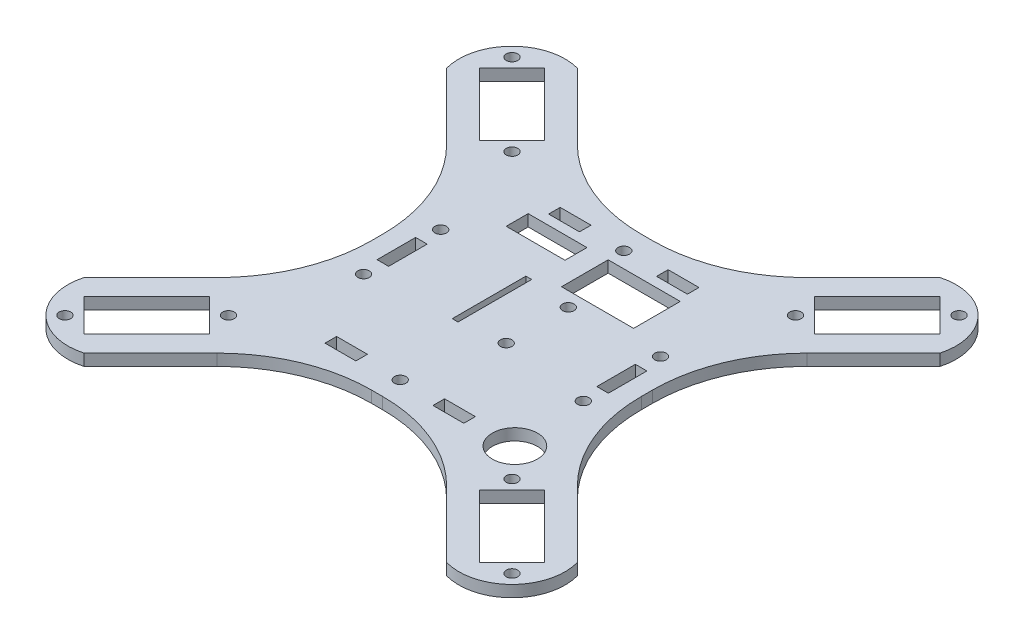
SolidWorks part; units mm, degrees
material "Pinho"
ref_plane "Plano frontal" through (0, 0, 0) normal (0, 0, 1) x (1, 0, 0)
ref_plane "Plano superior" through (0, 0, 0) normal (0, 1, 0) x (1, 0, 0)
ref_plane "Plano direito" through (0, 0, 0) normal (1, 0, 0) x (0, 0, -1)
sketch "Esboço1" plane through (0, 0, 0) normal (0, 1, 0) x (1, 0, 0)
  line L1 (84.8478, -7) -> (84.8478, 3)
  line L2 (121.8478, -29.5) -> (121.8478, -32.5)
  line L3 (129.8478, -32.5) -> (121.8478, -32.5)
  line L4 (129.8478, -29.5) -> (129.8478, -32.5)
  line L5 (110.3869, 33) -> (113.3087, 33)
  line L6 (76.8478, -0.5391) -> (76.8478, -3.4609)
  line L7 (110.3869, -37) -> (113.3087, -37)
  line L8 (146.8478, -0.5391) -> (146.8478, -3.4609)
  line L9 (129.8478, -29.5) -> (121.8478, -29.5)
  line L10 (84.8478, -7) -> (81.8478, -7)
  line L11 (81.8478, -7) -> (81.8478, 3)
  line L12 (84.8478, 3) -> (81.8478, 3)
  line L13 (141.8478, -7) -> (141.8478, 3)
  line L14 (141.8478, -7) -> (138.8478, -7)
  line L15 (138.8478, -7) -> (138.8478, 3)
  line L16 (93.8478, -29.5) -> (101.8478, -29.5)
  line L17 (141.8478, 3) -> (138.8478, 3)
  line L18 (101.8478, 25.5) -> (101.8478, 28.5)
  line L19 (93.8478, 28.5) -> (101.8478, 28.5)
  line L20 (93.8478, 25.5) -> (93.8478, 28.5)
  line L21 (106.3478, 22.9447) -> (91.0978, 22.9447)
  line L22 (93.8478, 25.5) -> (101.8478, 25.5)
  line L23 (106.3478, 22.9447) -> (106.3478, 17.2447)
  line L24 (106.3478, 17.2447) -> (91.0978, 17.2447)
  line L25 (91.0978, 22.9447) -> (91.0978, 17.2447)
  line L26 (129.8478, 25.5) -> (121.8478, 25.5)
  line L27 (129.8478, 25.5) -> (129.8478, 28.5)
  line L28 (129.8478, 28.5) -> (121.8478, 28.5)
  line L29 (121.8478, 25.5) -> (121.8478, 28.5)
  line L32 (130.5478, 10.8447) -> (111.8478, 10.8447)
  line L33 (111.8478, 22.9447) -> (111.8478, 10.8447)
  line L34 (130.5478, 22.9447) -> (111.8478, 22.9447)
  line L35 (130.5478, 22.9447) -> (130.5478, 10.8447)
  line L37 (165.604, -59.256) -> (169.1216, -55.7383)
  line L38 (146.8478, -45.4853) -> (155.3331, -37)
  line L39 (163.1112, -61.7487) -> (165.604, -59.256)
  line L40 (171.5965, -53.2635) -> (169.1216, -55.7383)
  line L41 (47.8564, 45.0208) -> (65.1321, 27.7452)
  line L42 (64.827, -65.9914) -> (82.1026, -48.7157)
  line L43 (163.1112, -61.7487) -> (146.8478, -45.4853)
  line L44 (163.4648, -45.1317) -> (171.5965, -53.2635)
  line L45 (163.4648, -45.1317) -> (155.3331, -37)
  line L46 (158.8686, -65.9914) -> (141.593, -48.7157)
  line L47 (65.1321, -31.7452) -> (47.8564, -49.0208)
  line L48 (158.5635, -31.7452) -> (175.8392, -49.0208)
  line L49 (158.8686, 61.9914) -> (141.593, 44.7157)
  line L50 (163.4648, 41.1317) -> (155.3331, 33)
  line L51 (163.4648, 41.1317) -> (171.5965, 49.2635)
  line L52 (163.1112, 57.7487) -> (146.8478, 41.4853)
  line L53 (175.8392, 45.0208) -> (158.5635, 27.7452)
  line L54 (104.8478, 8.6) -> (104.8478, -10.5)
  line L55 (171.5965, 49.2635) -> (169.1216, 51.7383)
  line L56 (163.1112, 57.7487) -> (165.604, 55.256)
  line L57 (146.8478, 41.4853) -> (155.3331, 33)
  line L58 (93.8478, -29.5) -> (93.8478, -32.5)
  line L59 (93.8478, -32.5) -> (101.8478, -32.5)
  line L60 (101.8478, -29.5) -> (101.8478, -32.5)
  line L61 (165.604, 55.256) -> (169.1216, 51.7383)
  line L62 (104.8478, -10.5) -> (106.3478, -10.5)
  line L63 (64.827, 61.9914) -> (82.1026, 44.7157)
  line L64 (106.3478, -10.5) -> (106.3478, 7.8737)
  line L65 (68.7161, 49.617) -> (76.8478, 41.4853)
  line L66 (68.7161, 49.617) -> (60.5843, 57.7487)
  line L67 (52.099, 49.2635) -> (68.3625, 33)
  line L72 (106.3478, 8.6) -> (104.8478, 8.6)
  line L73 (106.3478, 8.6) -> (106.3478, 7.8737)
  line L74 (60.5843, 57.7487) -> (58.1095, 55.2739)
  line L75 (52.099, 49.2635) -> (54.5918, 51.7562)
  line L76 (68.3625, 33) -> (76.8478, 41.4853)
  line L77 (54.5918, 51.7562) -> (58.1095, 55.2739)
  line L90 (54.5918, -55.7562) -> (58.1095, -59.2739)
  line L91 (68.3625, -37) -> (76.8478, -45.4853)
  line L93 (52.099, -53.2635) -> (54.5918, -55.7562)
  line L94 (60.5843, -61.7487) -> (58.1095, -59.2739)
  line L110 (52.099, -53.2635) -> (68.3625, -37)
  line L111 (68.7161, -53.617) -> (60.5843, -61.7487)
  line L112 (68.7161, -53.617) -> (76.8478, -45.4853)
  circle A0 centre (111.8478, 27) radius 1.5
  circle A1 centre (111.8478, -31) radius 1.5
  arc A2 (158.8686, -65.9914) -> (175.8392, -49.0208) centre (162.5557, -52.7079) ccw
  circle A3 centre (169.8287, -59.9809) radius 1.5
  circle A4 centre (148.6156, -38.7678) radius 1.5
  circle A5 centre (148.6156, 34.7678) radius 1.5
  circle A6 centre (169.8287, 55.9809) radius 1.5
  arc A7 (158.8686, 61.9914) -> (175.8392, 45.0208) centre (162.5557, 48.7079) cw
  circle A8 centre (75.08, 34.7678) radius 1.5
  circle A9 centre (53.8669, 55.9809) radius 1.5
  arc A10 (47.8564, 45.0208) -> (64.827, 61.9914) centre (61.1399, 48.7079) cw
  arc A11 (110.3869, 33) -> (82.1026, 44.7157) centre (110.3869, 73) cw
  arc A12 (113.3087, 33) -> (141.593, 44.7157) centre (113.3087, 73) ccw
  arc A13 (113.3087, -37) -> (141.593, -48.7157) centre (113.3087, -77) cw
  arc A14 (110.3869, -37) -> (82.1026, -48.7157) centre (110.3869, -77) ccw
  arc A15 (76.8478, -0.5391) -> (65.1321, 27.7452) centre (36.8478, -0.5391) ccw
  arc A16 (76.8478, -3.4609) -> (65.1321, -31.7452) centre (36.8478, -3.4609) cw
  arc A17 (146.8478, -0.5391) -> (158.5635, 27.7452) centre (186.8478, -0.5391) cw
  arc A18 (146.8478, -3.4609) -> (158.5635, -31.7452) centre (186.8478, -3.4609) ccw
  circle A19 centre (117.3478, 7.1) radius 1.5
  arc A20 (47.8564, -49.0208) -> (64.827, -65.9914) centre (61.1399, -52.7079) ccw
  circle A21 centre (53.8669, -59.9809) radius 1.5
  circle A22 centre (75.08, -38.7678) radius 1.5
  circle A23 centre (117.3478, -9) radius 1.5
  circle A24 centre (83.3478, 8) radius 1.5
  circle A25 centre (83.3478, -12) radius 1.5
  circle A26 centre (140.3478, 8) radius 1.5
  circle A27 centre (140.3478, -12) radius 1.5
  circle A28 centre (141.593, -31) radius 5.85
  dimension "D1" = 40
  dimension "D2" = 40
  dimension "D3" = 40
  dimension "D4" = 40
  dimension "D5" = 40
  dimension "D6" = 40
  dimension "D7" = 40
  dimension "D8" = 40
extrude "Ressalto-extrusão1" add sketch "Esboço1" along normal blind 3
